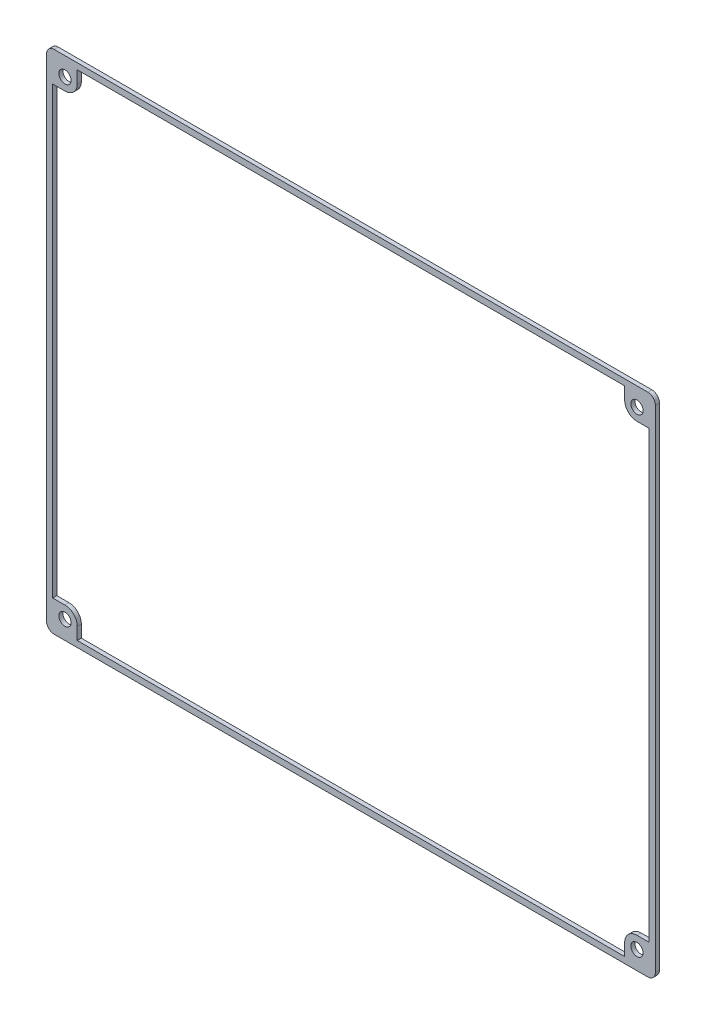
SolidWorks part; units mm, degrees
material "Teak"
ref_plane "Front Plane" through (0, 0, 0) normal (0, 0, 1) x (1, 0, 0)
ref_plane "Top Plane" through (0, 0, 0) normal (0, 1, 0) x (1, 0, 0)
ref_plane "Right Plane" through (0, 0, 0) normal (1, 0, 0) x (0, 0, -1)
sketch "Sketch1" plane through (0, 0, 0) normal (0, 0, 1) x (1, 0, 0)
  line L2 (-3.7366, 240) -> (-3.7366, 0) construction
  line L4 (290, -0.7366) -> (0, -0.7366) construction
  line L6 (0, -3.7366) -> (290, -3.7366) construction
  line L10 (0, 240.7366) -> (290, 240.7366) construction
  line L11 (0, 243.7366) -> (290, 243.7366) construction
  line L14 (-3.7366, 240) -> (-3.7366, 0)
  line L16 (278.7366, -0.7366) -> (11.2634, -0.7366)
  line L18 (0, -3.7366) -> (290, -3.7366)
  line L20 (278.7366, 234.7366) -> (278.7366, 240.7366)
  line L21 (284.7366, 228.7366) -> (290.7366, 228.7366)
  line L22 (11.2634, 240.7366) -> (278.7366, 240.7366)
  line L23 (0, 243.7366) -> (290, 243.7366)
  line L26 (293.7366, 120) -> (-3.7366, 120) construction
  line L27 (145, 243.7366) -> (145, -3.7366) construction
  line L28 (290.7366, 240) -> (290.7366, 0)
  line L29 (290.7366, 0) -> (293.7366, 0)
  line L30 (293.7366, 0) -> (293.7366, 240)
  line L31 (293.7366, 240) -> (290.7366, 240)
  line L32 (290.7366, 228.7366) -> (290.7366, 11.2634)
  line L34 (293.7366, 0) -> (293.7366, 240)
  line L36 (278.7366, 5.2634) -> (278.7366, -0.7366)
  line L37 (284.7366, 11.2634) -> (290.7366, 11.2634)
  line L38 (11.2634, 234.7366) -> (11.2634, 240.7366)
  line L39 (5.2634, 228.7366) -> (-0.7366, 228.7366)
  line L40 (11.2634, 5.2634) -> (11.2634, -0.7366)
  line L41 (5.2634, 11.2634) -> (-0.7366, 11.2634)
  line L42 (-0.7366, 11.2634) -> (-0.7366, 228.7366)
  circle A0 centre (5.2634, 234.7366) radius 6 construction
  circle A1 centre (5.2634, 5.2634) radius 6 construction
  circle A2 centre (284.7366, 5.2634) radius 6 construction
  circle A3 centre (284.7366, 5.2634) radius 3 construction
  circle A4 centre (284.7366, 234.7366) radius 3 construction
  arc A5 (5.2634, 228.7366) -> (11.2634, 234.7366) centre (5.2634, 234.7366) ccw
  arc A6 (11.2634, 5.2634) -> (5.2634, 11.2634) centre (5.2634, 5.2634) ccw
  arc A7 (284.7366, 11.2634) -> (278.7366, 5.2634) centre (284.7366, 5.2634) ccw
  circle A8 centre (284.7366, 5.2634) radius 3
  circle A9 centre (284.7366, 234.7366) radius 3
  circle A10 centre (284.7366, 234.7366) radius 6 construction
  arc A11 (278.7366, 234.7366) -> (284.7366, 228.7366) centre (284.7366, 234.7366) ccw
  arc A12 (290, 243.7366) -> (293.7366, 240) centre (290, 240) cw
  arc A13 (290, -3.7366) -> (293.7366, 0) centre (290, 0) ccw
  arc A14 (0, 243.7366) -> (-3.7366, 240) centre (0, 240) ccw
  arc A15 (0, -3.7366) -> (-3.7366, 0) centre (0, 0) cw
  circle A16 centre (5.2634, 234.7366) radius 3 construction
  circle A17 centre (5.2634, 234.7366) radius 3
  circle A18 centre (5.2634, 5.2634) radius 3 construction
  circle A19 centre (5.2634, 5.2634) radius 3
  point P48 (287.7366, 228.7366)
  point P49 (278.7366, 237.7366)
  point P50 (11.2634, 237.7366)
  point P53 (2.2634, 228.7366)
  dimension "D1" = 0
extrude "Boss-Extrude1" add sketch "Sketch1" along normal blind 2
